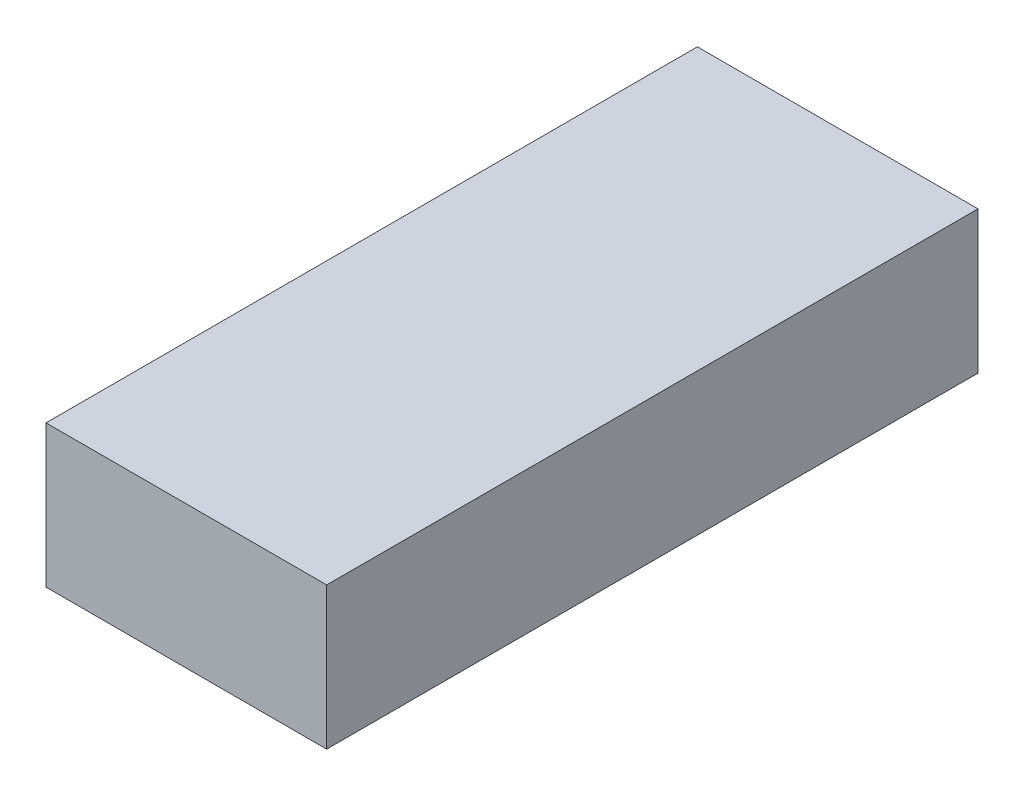
SolidWorks part; units mm, degrees
ref_plane "Спереди" through (0, 0, 0) normal (0, 0, 1) x (1, 0, 0)
ref_plane "Сверху" through (0, 0, 0) normal (0, 1, 0) x (1, 0, 0)
ref_plane "Справа" through (0, 0, 0) normal (1, 0, 0) x (0, 0, -1)
sketch "Эскиз2" plane through (0, 0, 0) normal (0, 0, 1) x (1, 0, 0)
  line L1 (-61.4499, 31.1677) -> (67.8251, 31.1677)
  line L2 (-61.4499, 31.1677) -> (-61.4499, -34.3553)
  line L3 (-61.4499, -34.3553) -> (67.8251, -34.3553)
  line L4 (67.8251, 31.1677) -> (67.8251, -34.3553)
extrude "Бобышка-Вытянуть1" add sketch "Эскиз2" along normal blind 300
